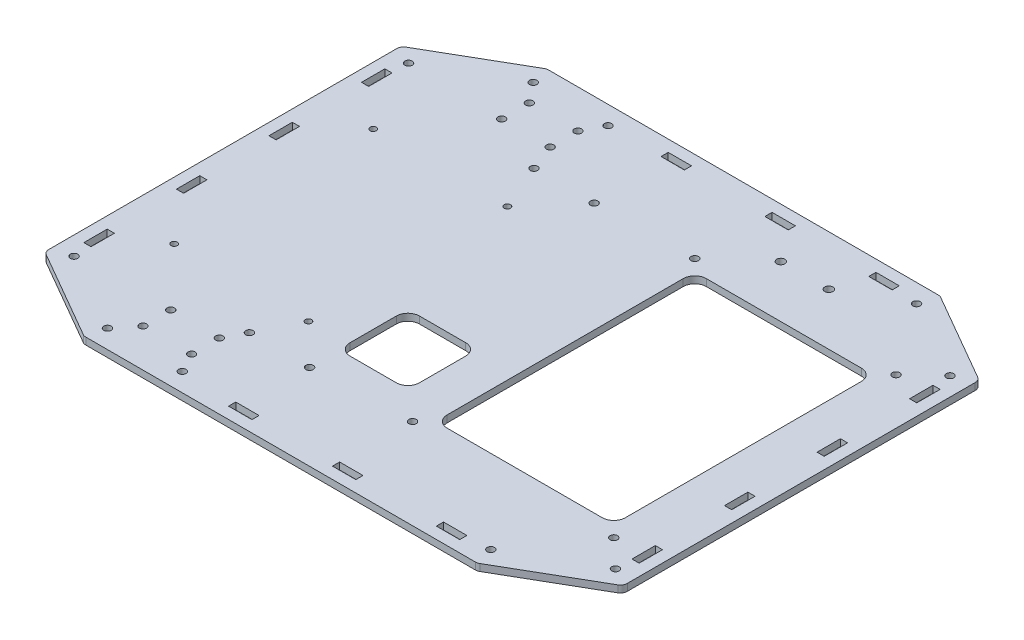
SolidWorks part; units mm, degrees
ref_plane "Front Plane" through (0, 0, 0) normal (0, 0, 1) x (1, 0, 0)
ref_plane "Top Plane" through (0, 0, 0) normal (0, 1, 0) x (1, 0, 0)
ref_plane "Right Plane" through (0, 0, 0) normal (1, 0, 0) x (0, 0, -1)
sketch "Sketch1" plane through (0, 0, 0) normal (0, 1, 0) x (1, 0, 0)
  line L0 (-85, 100) -> (85, 100)
  line L1 (-125, 100) -> (125, 100) construction
  line L2 (-125, 100) -> (-125, -100) construction
  line L3 (-125, -100) -> (125, -100) construction
  line L4 (125, 100) -> (125, -100) construction
  line L5 (85, 100) -> (125, 76.906)
  line L6 (125, 76.906) -> (125, -76.906)
  line L8 (-125, -76.906) -> (-125, 76.906)
  line L9 (-125, 76.906) -> (-85, 100)
  line L10 (-125, 0) -> (125, 0) construction
  line L11 (85, -100) -> (125, -76.906)
  line L12 (-85, -100) -> (85, -100)
  line L13 (-125, -76.906) -> (-85, -100)
  line L14 (0, 100) -> (0, -100) construction
  line L26 (-17.4, -91.9) -> (-27.5, -91.9)
  line L27 (-17.4, -91.9) -> (-17.4, -95)
  line L28 (-17.4, -95) -> (-27.5, -95)
  line L29 (-27.5, -91.9) -> (-27.5, -95)
  line L65 (-118.45, 14.95) -> (-118.45, -14.95) construction
  line L66 (-120, 65.05) -> (-116.9, 65.05)
  line L67 (-120, 65.05) -> (-120, 54.95)
  line L68 (-120, 54.95) -> (-116.9, 54.95)
  line L69 (-116.9, 65.05) -> (-116.9, 54.95)
  line L70 (-120, 25.05) -> (-116.9, 25.05)
  line L71 (-120, 25.05) -> (-120, 14.95)
  line L72 (-120, 14.95) -> (-116.9, 14.95)
  line L73 (-116.9, 25.05) -> (-116.9, 14.95)
  line L74 (-120, -14.95) -> (-116.9, -14.95)
  line L75 (-120, -14.95) -> (-120, -25.05)
  line L76 (-120, -25.05) -> (-116.9, -25.05)
  line L77 (-116.9, -14.95) -> (-116.9, -25.05)
  line L78 (-120, -54.95) -> (-116.9, -54.95)
  line L79 (-120, -54.95) -> (-120, -65.05)
  line L80 (-120, -65.05) -> (-116.9, -65.05)
  line L81 (-116.9, -54.95) -> (-116.9, -65.05)
  line L82 (120, -65.05) -> (116.9, -65.05)
  line L83 (116.9, -54.95) -> (116.9, -65.05)
  line L84 (120, -54.95) -> (116.9, -54.95)
  line L85 (120, -54.95) -> (120, -65.05)
  line L86 (120, -25.05) -> (116.9, -25.05)
  line L87 (116.9, -14.95) -> (116.9, -25.05)
  line L88 (120, -14.95) -> (116.9, -14.95)
  line L89 (120, -14.95) -> (120, -25.05)
  line L90 (120, 14.95) -> (116.9, 14.95)
  line L91 (116.9, 25.05) -> (116.9, 14.95)
  line L92 (120, 25.05) -> (116.9, 25.05)
  line L93 (120, 25.05) -> (120, 14.95)
  line L94 (120, 54.95) -> (116.9, 54.95)
  line L95 (116.9, 65.05) -> (116.9, 54.95)
  line L96 (120, 65.05) -> (116.9, 65.05)
  line L97 (120, 65.05) -> (120, 54.95)
  line L98 (27.5, -91.9) -> (27.5, -95)
  line L99 (27.5, -91.9) -> (17.4, -91.9)
  line L100 (17.4, -91.9) -> (17.4, -95)
  line L101 (27.5, -95) -> (17.4, -95)
  line L102 (72.4, -91.9) -> (72.4, -95)
  line L103 (72.4, -91.9) -> (62.3, -91.9)
  line L104 (62.3, -91.9) -> (62.3, -95)
  line L105 (72.4, -95) -> (62.3, -95)
  line L106 (72.4, 91.9) -> (62.3, 91.9)
  line L107 (62.3, 91.9) -> (62.3, 95)
  line L108 (72.4, 95) -> (62.3, 95)
  line L109 (72.4, 91.9) -> (72.4, 95)
  line L110 (27.5, 91.9) -> (17.4, 91.9)
  line L111 (17.4, 91.9) -> (17.4, 95)
  line L112 (27.5, 95) -> (17.4, 95)
  line L113 (27.5, 91.9) -> (27.5, 95)
  line L114 (-17.4, 95) -> (-27.5, 95)
  line L115 (-27.5, 91.9) -> (-27.5, 95)
  line L116 (-17.4, 91.9) -> (-27.5, 91.9)
  line L117 (-17.4, 91.9) -> (-17.4, 95)
  line L118 (-78.5, 86) -> (-78.5, 69) construction
  line L119 (-52.5, 86) -> (-78.5, 86) construction
  line L120 (-52.5, 69) -> (-52.5, 86) construction
  line L121 (-78.5, 69) -> (-52.5, 69) construction
  line L122 (-78.5, 86) -> (-78.5, 69) construction
  line L123 (-52.5, 86) -> (-78.5, 86) construction
  line L124 (-52.5, 69) -> (-52.5, 86) construction
  line L125 (-78.5, 69) -> (-52.5, 69) construction
  line L126 (-78.5, 77.5) -> (-52.5, 77.5) construction
  line L127 (-52.5, -69) -> (-52.5, -86) construction
  line L128 (-78.5, -69) -> (-52.5, -69) construction
  line L129 (-78.5, -86) -> (-78.5, -69) construction
  line L130 (-52.5, -86) -> (-78.5, -86) construction
  line L131 (-78.5, -77.5) -> (-52.5, -77.5) construction
  circle A0 centre (-50.5, -63) radius 1.6 construction
  circle A1 centre (82.8564, 92) radius 1.6 construction
  circle A2 centre (117, 72.2872) radius 1.6 construction
  circle A3 centre (117, -72.2872) radius 1.6 construction
  circle A4 centre (82.8564, -92) radius 1.6 construction
  circle A5 centre (-24.5, -63) radius 1.6 construction
  circle A6 centre (-24.5, 60) radius 1.6 construction
  circle A7 centre (-117, -72.2872) radius 1.6 construction
  circle A8 centre (-50.5, -92) radius 1.6 construction
  circle A9 centre (-50.5, 60) radius 1.6 construction
  circle A10 centre (-117, 72.2872) radius 1.6 construction
  circle A11 centre (-50.5, 92) radius 1.6 construction
  circle A12 centre (-50.5, -63) radius 1.6
  circle A13 centre (82.8564, 92) radius 1.6
  circle A14 centre (117, 72.2872) radius 1.6
  circle A15 centre (117, -72.2872) radius 1.6
  circle A16 centre (82.8564, -92) radius 1.6
  circle A17 centre (-24.5, -63) radius 1.6
  circle A18 centre (-24.5, 60) radius 1.6
  circle A19 centre (-117, -72.2872) radius 1.6
  circle A20 centre (-50.5, -92) radius 1.6
  circle A21 centre (-50.5, 60) radius 1.6
  circle A22 centre (-117, 72.2872) radius 1.6
  circle A23 centre (-50.5, 92) radius 1.6
  circle A24 centre (-82.8564, -92) radius 1.6 construction
  circle A25 centre (-82.8564, 92) radius 1.6 construction
  circle A26 centre (-82.8564, -92) radius 1.6
  circle A27 centre (-82.8564, 92) radius 1.6
  circle A28 centre (-55, 71.5) radius 1.59 construction
  circle A29 centre (-76, 71.5) radius 1.59 construction
  circle A30 centre (-55, 71.5) radius 1.59
  circle A31 centre (-76, 71.5) radius 1.59
  circle A32 centre (-55, 83.5) radius 1.59
  circle A33 centre (-76, 83.5) radius 1.59
  circle A34 centre (-55, -83.5) radius 1.59
  circle A35 centre (-55, -71.5) radius 1.59
  circle A36 centre (-76, -71.5) radius 1.59
  circle A37 centre (-76, -83.5) radius 1.59
  circle A39 centre (37.7074, 78.475) radius 1.75 construction
  circle A40 centre (58.4574, 78.475) radius 1.75 construction
  circle A41 centre (37.7074, 78.475) radius 1.75
  circle A42 centre (58.4574, 78.475) radius 1.75
  point P4 (0, 100)
  point P6 (-125, 0)
  point P9 (0, 0)
  point P20 (-22.45, -95)
  point P61 (-116.9, 60)
  point P62 (-116.9, 20)
  point P63 (-116.9, -20)
  point P64 (-116.9, -60)
  point P67 (-118.45, 0)
  dimension "D1" = 250
  dimension "D2" = 200
  dimension "D3" = 60
  dimension "D4" = 60
  dimension "D5" = 40
  dimension "D6" = 10.1
  dimension "D7" = 3.1
  dimension "D8" = 22.45
  dimension "D9" = 3
  dimension "D10" = 5
  dimension "D11" = 3.1
  dimension "D12" = 10.1
  dimension "D13" = 5
  dimension "D14" = 40
  dimension "D15" = 40
  dimension "D16" = 40
extrude "Boss-Extrude1" add sketch "Sketch1" along normal blind 3
sketch "Sketch3" plane through (0, 3, 0) normal (0, 1, 0) x (1, 0, 0)
  line L0 (28, 56) -> (95, 56)
  line L1 (18, 61) -> (105, 61) construction
  line L2 (18, 61) -> (18, -61) construction
  line L3 (18, -61) -> (105, -61) construction
  line L4 (105, 61) -> (105, -61) construction
  line L5 (100, 51) -> (100, -51)
  line L6 (28, -56) -> (95, -56)
  line L7 (23, 51) -> (23, -51)
  line L8 (23, 56) -> (100, 56) construction
  line L9 (23, 56) -> (23, -56) construction
  line L10 (23, -56) -> (100, -56) construction
  line L11 (100, 56) -> (100, -56) construction
  line L17 (-20, -50) -> (0, -50)
  line L18 (-25, -45) -> (-25, -25)
  line L19 (-20, -20) -> (0, -20)
  line L20 (5, -45) -> (5, -25)
  arc A0 (28, 56) -> (23, 51) centre (28, 51) ccw
  arc A1 (28, -56) -> (23, -51) centre (28, -51) cw
  arc A2 (100, -51) -> (95, -56) centre (95, -51) cw
  arc A3 (95, 56) -> (100, 51) centre (95, 51) cw
  arc A4 (-20, -50) -> (-25, -45) centre (-20, -45) cw
  arc A5 (0, -50) -> (5, -45) centre (0, -45) ccw
  arc A6 (0, -20) -> (5, -25) centre (0, -25) cw
  arc A7 (-25, -25) -> (-20, -20) centre (-20, -25) cw
  point P27 (-25, -50)
  point P32 (5, -20)
  point P35 (-25, -20)
  line B0 (-25, -50) -> (-104, -50) construction
  line B1 (-25, -50) -> (-25, 50) construction
  line B2 (-25, 50) -> (-104, 50) construction
  line B3 (-104, -50) -> (-104, 50) construction
  circle B4 centre (-100, -46) radius 1.35
  circle B5 centre (-42, -46) radius 1.35
  circle B6 centre (-42, 40) radius 1.35
  circle B7 centre (-100, 40) radius 1.35
  line B8 (14, 65) -> (14, -65) construction
  line B9 (14, 65) -> (109, 65) construction
  circle B10 centre (18, 61) radius 1.6
  circle B11 centre (105, 61) radius 1.6
  circle B12 centre (105, -61) radius 1.6
  circle B13 centre (18, -61) radius 1.6
  dimension "D4" = 5
  dimension "D5" = 5
  dimension "D7" = 5
  dimension "D1" = 25
  dimension "D2" = 14
  dimension "D6" = 30
  dimension "D3" = 5
sketch_block_instance "Block-Jetson-Nano-1"
sketch_block "Block-Jetson-Nano"
sketch_block_instance "Block-MCU-Board-1"
sketch_block "Block2" parameters "D3"=3.2, "D1"=87, "D2"=122
extrude "Cut-Extrude1" cut sketch "Sketch3" against normal up to next
fillet "Fillet1" radius 3 8 edges at (85, 1.5, -100) (125, 1.5, -76.906) (-85, 1.5, -100) (-125, 1.5, -76.906) (-85, 1.5, 100) (-125, 1.5, 76.906) (85, 1.5, 100) (125, 1.5, 76.906)
